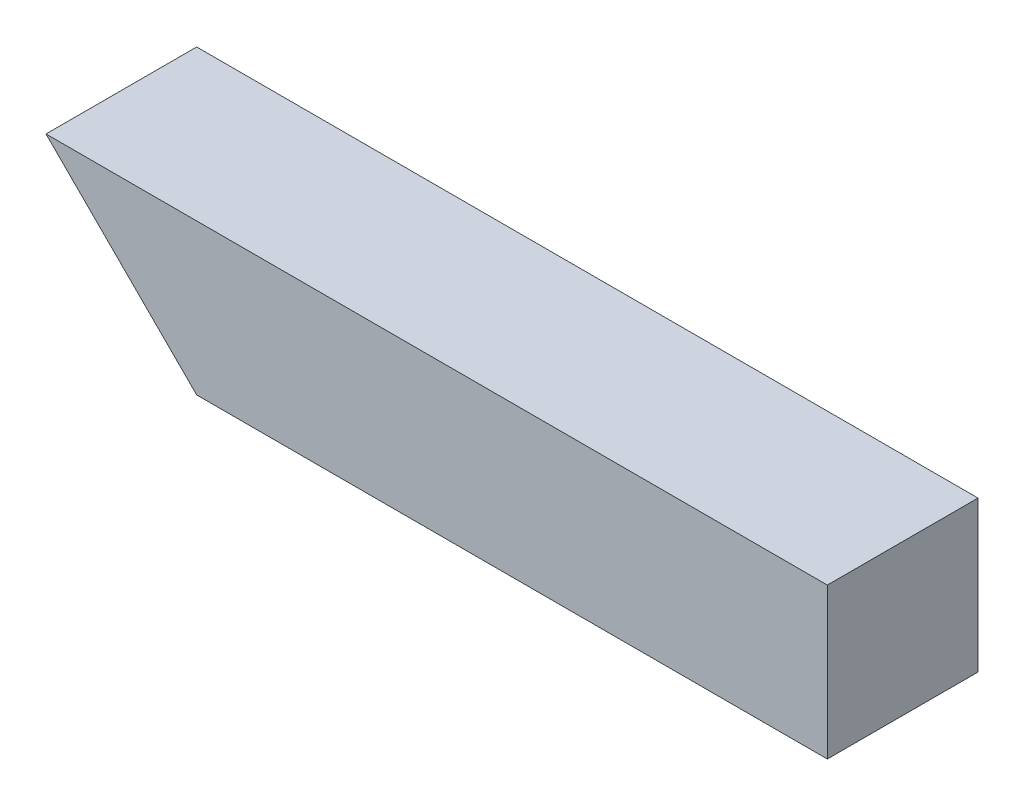
SolidWorks part; units mm, degrees
ref_plane "Front Plane" through (0, 0, 0) normal (0, 0, 1) x (1, 0, 0)
ref_plane "Top Plane" through (0, 0, 0) normal (0, 1, 0) x (1, 0, 0)
ref_plane "Right Plane" through (0, 0, 0) normal (1, 0, 0) x (0, 0, -1)
sketch "Sketch1" plane through (0, 0, 0) normal (1, 0, 0) x (0, 0, -1)
  line L1 (0, 0) -> (38.1, 0)
  line L2 (0, 0) -> (0, -38.1)
  line L3 (0, -38.1) -> (38.1, -38.1)
  line L4 (38.1, 0) -> (38.1, -38.1)
  dimension "D1" = 38.1
  dimension "D2" = 38.1
extrude "Boss-Extrude1" add sketch "Sketch1" along normal blind 197.5656
sketch "Sketch2" plane through (0, 0, 0) normal (0, 0, 1) x (1, 0, 0)
  line L0 (0, -38.1) -> (38.1, -38.1)
  line L1 (197.5656, -38.1) -> (0, -38.1) construction
  line L2 (38.1, -38.1) -> (0, 0)
  dimension "D1" = 38.1
extrude "Cut-Extrude1" cut sketch "Sketch2" against normal through all and the other way through all
